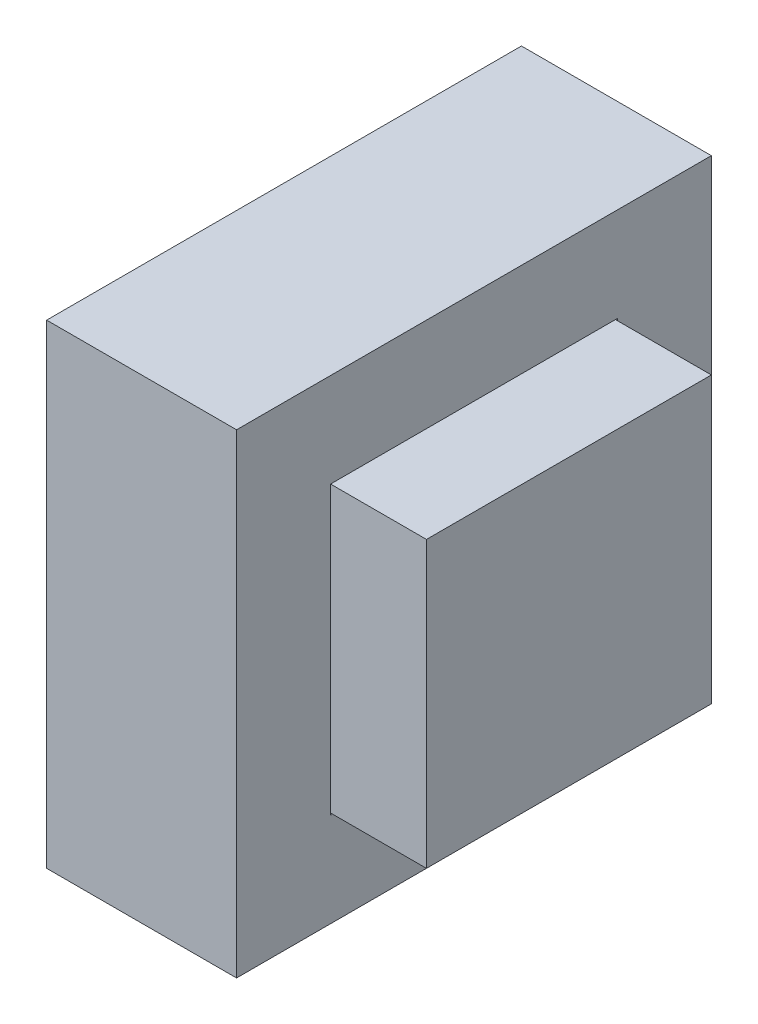
SolidWorks part; units mm, degrees
ref_plane "前视基准面" through (0, 0, 0) normal (0, 0, 1) x (1, 0, 0)
ref_plane "上视基准面" through (0, 0, 0) normal (0, 1, 0) x (1, 0, 0)
ref_plane "右视基准面" through (0, 0, 0) normal (1, 0, 0) x (0, 0, -1)
other "Configuration Table"
sketch "草图1" plane through (0, 0, 0) normal (1, 0, 0) x (0, 0, -1)
  line L1 (-25, 25) -> (25, 25)
  line L2 (-25, 25) -> (-25, -25)
  line L3 (-25, -25) -> (25, -25)
  line L4 (25, 25) -> (25, -25)
  line L5 (-25, 25) -> (25, -25) construction
  line L6 (-25, -25) -> (25, 25) construction
  point P0 (0, 0)
  dimension "D1" = 50
  dimension "D2" = 50
extrude "凸台-拉伸1" add sketch "草图1" along normal blind 20
sketch "草图2" plane through (20, 0, 0) normal (1, 0, 0) x (0, 0, -1)
  line L0 (15, -15) -> (15, 15)
  line L5 (15, 15) -> (-15, 15)
  line L6 (-15, 15) -> (-15, -15)
  line L7 (-15, -15) -> (15, -15)
  line L8 (25, -25) -> (25, 25)
  line L9 (25, 25) -> (-25, 25)
  line L10 (-25, 25) -> (-25, -25)
  line L11 (-25, -25) -> (25, -25)
  line L12 (25, -25) -> (25, 25)
  line L13 (25, 25) -> (-25, 25)
  line L14 (-25, 25) -> (-25, -25)
  line L15 (-25, -25) -> (25, -25)
  point P0 (0, 0)
  dimension "D1" = 0
  dimension "D2" = 10
extrude "凸台-拉伸2" add sketch "草图2" along normal blind 10 contours L0 L5 L6 L7
sketch "草图3" plane through (30, 0, 0) normal (1, 0, 0) x (0, 0, -1)
  line L0 (-15.1, -15.1) -> (15.1, -15.1)
  line L1 (15.1, -15.1) -> (15.1, 15.1)
  line L2 (15.1, 15.1) -> (-15.1, 15.1)
  line L3 (-15.1, 15.1) -> (-15.1, -15.1)
  line L4 (-15, -15) -> (15, -15)
  line L5 (15, -15) -> (15, 15)
  line L6 (15, 15) -> (-15, 15)
  line L7 (-15, 15) -> (-15, -15)
  line L8 (-15, -15) -> (15, -15)
  line L9 (15, -15) -> (15, 15)
  line L10 (15, 15) -> (-15, 15)
  line L11 (-15, 15) -> (-15, -15)
  dimension "D1" = 0
  dimension "D2" = 0.1
extrude "切除-拉伸1" cut sketch "草图3" against normal blind 15
